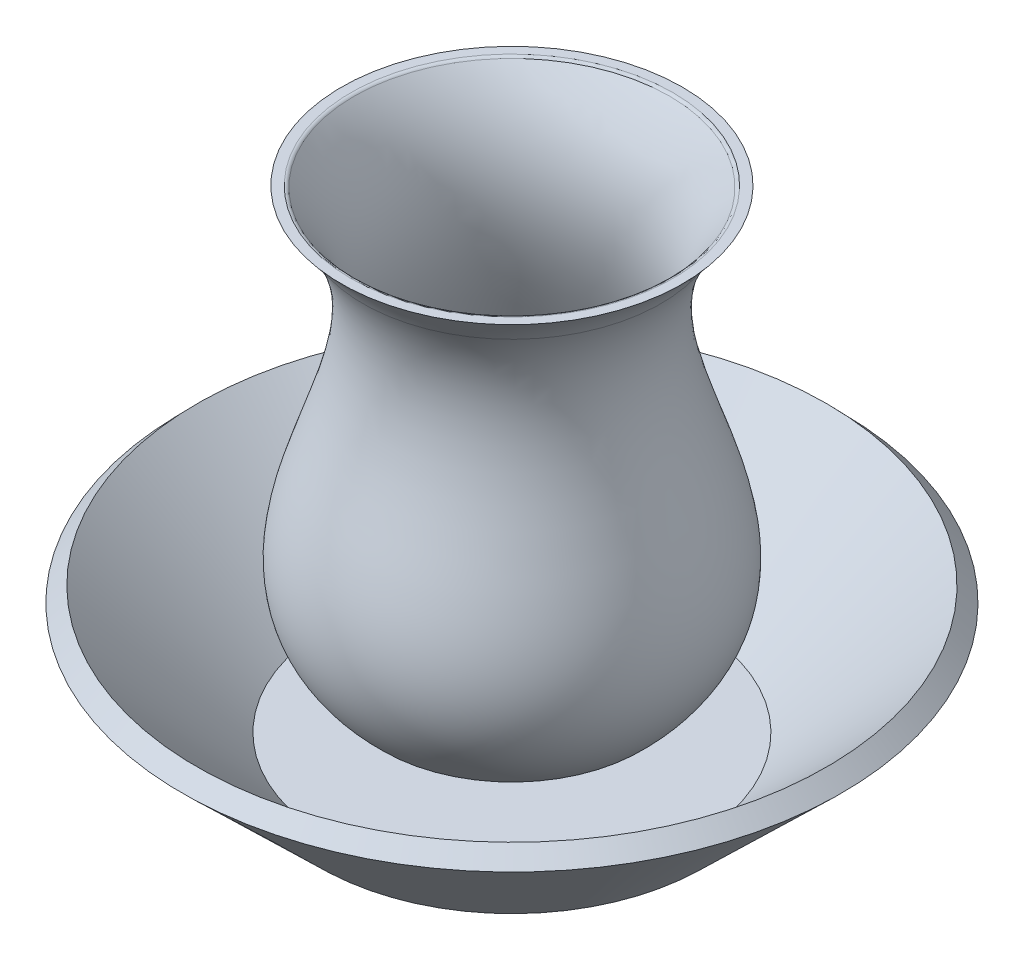
SolidWorks part; units mm, degrees
other "Markup1"
sketch "Sketch2" plane through (-46.815, 100, 46.815) normal (-0.8425, 0.3723, 0.3893) x (0.4224, 0.0081, 0.9064)
material "A-Glass Fiber"
ref_plane "Front Plane" through (0, 0, 0) normal (0, 0, 1) x (1, 0, 0)
ref_plane "Top Plane" through (0, 0, 0) normal (0, 1, 0) x (1, 0, 0)
ref_plane "Right Plane" through (0, 0, 0) normal (1, 0, 0) x (0, 0, -1)
sketch "Sketch1" plane through (0, 0, 0) normal (0, 0, 1) x (1, 0, 0)
  line L0 (0, 0) -> (0, 100) construction
  line L1 (40, 100) -> (0, 100)
  line L2 (30, 0) -> (0, 0)
  line L3 (0, 0) -> (0, 100)
  spline S0 degree 3 poles (40, 100) (8.2143, 65.6764) (63.63, 31.7032) (30, 0) knots 0 0 0 0 1 1 1 1
  dimension "D1" = 100
  dimension "D2" = 40
  dimension "D3" = 30
revolve "Revolve2" add sketch "Sketch1" angle 360 about L0
shell "Shell26" thickness 2
fillet "Fillet1" radius 1 2 edges at (0, 2, -29.1966) (0, 100, -37.3174)
ref_plane "Plane1" through (0, 93.4587, 0) normal (0, 1, 0) x (1, 0, 0)
split line "Split Line17"
sketch "Sketch7" plane through (0, 0, 0) normal (0, 0, 1) x (1, 0, 0)
  line L0 (0, -16.1252) -> (-45, -16.1252)
  line L1 (-45, -16.1252) -> (-77.3218, 15.1846)
  line L2 (0, -16.1252) -> (0, 0) construction
  dimension "D1" = 45
  dimension "D2" = 45
revolve "Revolve-Thin2" add sketch "Sketch7" angle 360 about L2
